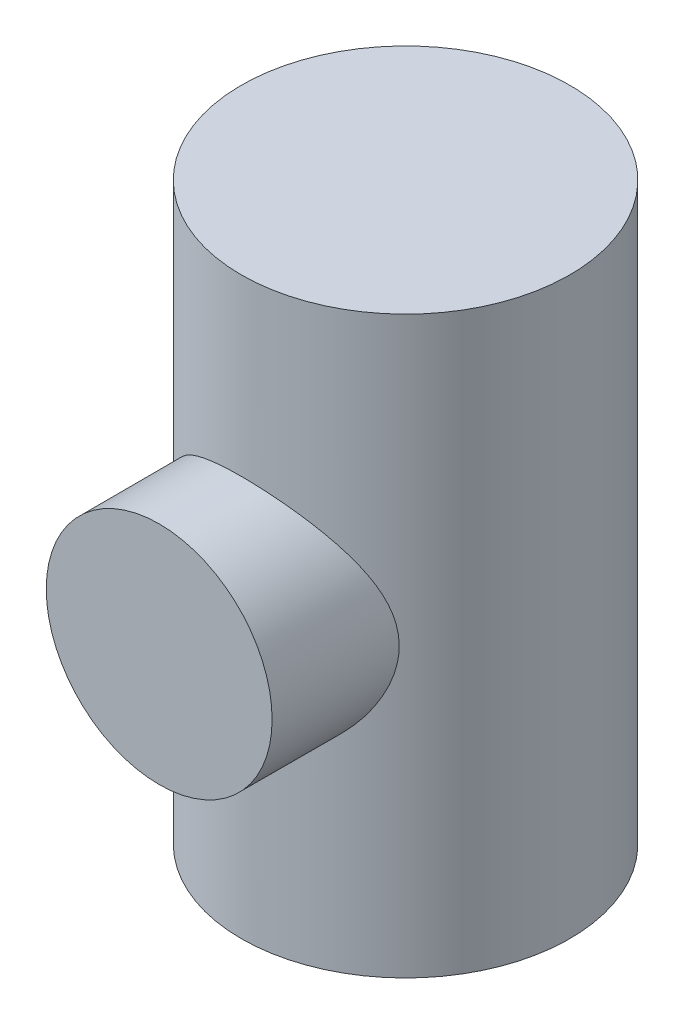
SolidWorks part; units mm, degrees
ref_plane "Front Plane" through (0, 0, 0) normal (0, 0, 1) x (1, 0, 0)
ref_plane "Top Plane" through (0, 0, 0) normal (0, 1, 0) x (1, 0, 0)
ref_plane "Right Plane" through (0, 0, 0) normal (1, 0, 0) x (0, 0, -1)
sketch "Sketch1" plane through (0, 0, 0) normal (0, 1, 0) x (1, 0, 0)
  circle A0 centre (0, 0) radius 50.8
  dimension "D1" = 101.6
extrude "Boss-Extrude1" add sketch "Sketch1" along normal mid plane 177.8
sketch "Sketch2" plane through (0, 0, 0) normal (0, 0, 1) x (1, 0, 0)
  circle A0 centre (0, 0) radius 34.925
  dimension "D1" = 69.85
extrude "Boss-Extrude2" add sketch "Sketch2" along normal blind 76.2
